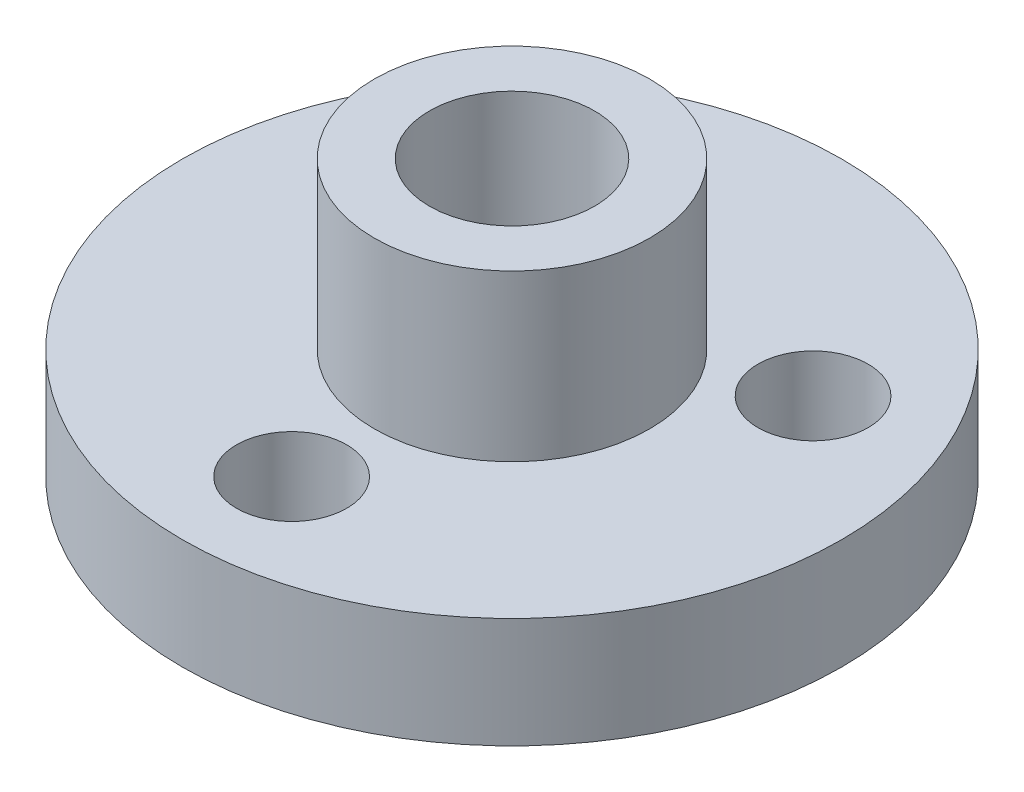
SolidWorks part; units mm, degrees
ref_plane "Front Plane" through (0, 0, 0) normal (0, 0, 1) x (1, 0, 0)
ref_plane "Top Plane" through (0, 0, 0) normal (0, 1, 0) x (1, 0, 0)
ref_plane "Right Plane" through (0, 0, 0) normal (1, 0, 0) x (0, 0, -1)
sketch "Sketch1" plane through (0, 0, 0) normal (0, 1, 0) x (1, 0, 0)
  circle A0 centre (0, 0) radius 9.5
  dimension "D1" = 19
extrude "Boss-Extrude1" add sketch "Sketch1" along normal blind 3.18
sketch "Sketch2" plane through (0, 3.18, 0) normal (0, 1, 0) x (1, 0, 0)
  circle A0 centre (0, 0) radius 3.97
  dimension "D1" = 7.94
extrude "Boss-Extrude2" add sketch "Sketch2" along normal blind 4.76
sketch "Sketch3" plane through (0, 7.94, 0) normal (0, 1, 0) x (1, 0, 0)
  circle A0 centre (0, 0) radius 2.38
  dimension "D1" = 4.76
extrude "Cut-Extrude1" cut sketch "Sketch3" against normal through all
sketch "Sketch4" plane through (0, 3.18, 0) normal (0, 1, 0) x (1, 0, 0)
  circle A0 centre (0, 0) radius 6.35 construction
  circle A1 centre (0, -6.35) radius 1.5875
  circle A2 centre (-5.4993, 3.175) radius 1.5875
  circle A3 centre (5.4993, 3.175) radius 1.5875
  point P12 (0, 0)
  dimension "D1" = 12.7
  dimension "D2" = 3.175
  dimension "D3" = 3
extrude "Cut-Extrude2" cut sketch "Sketch4" against normal through all
